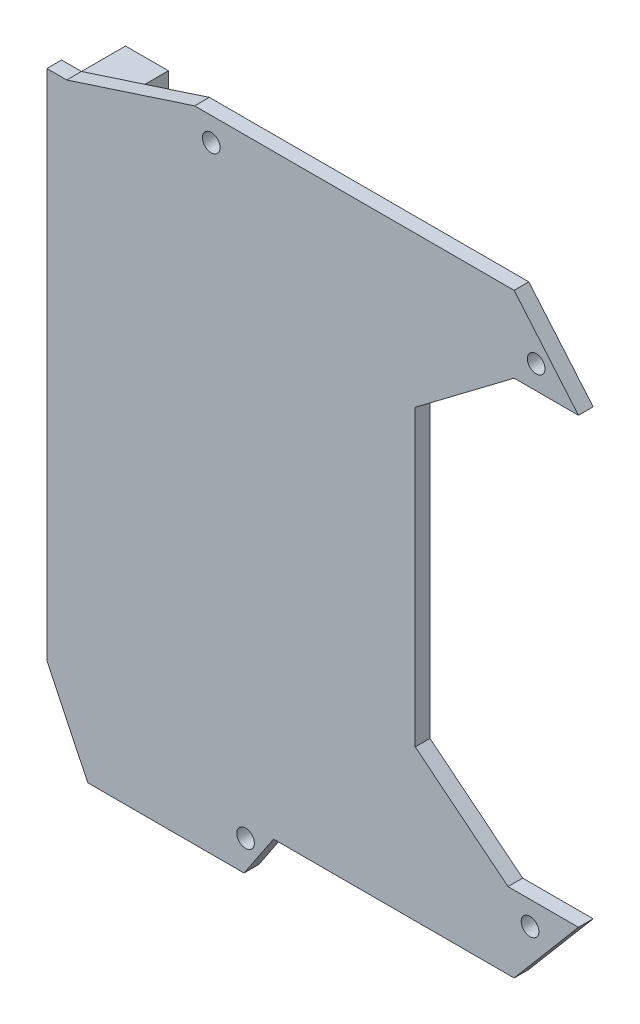
SolidWorks part; units mm, degrees
ref_plane "前视基准面" through (0, 0, 0) normal (0, 0, 1) x (1, 0, 0)
ref_plane "上视基准面" through (0, 0, 0) normal (0, 1, 0) x (1, 0, 0)
ref_plane "右视基准面" through (0, 0, 0) normal (1, 0, 0) x (0, 0, -1)
other "Configuration Table"
sketch "草图1" plane through (0, 0, 0) normal (0, 0, 1) x (1, 0, 0)
  line L0 (-117.8959, 10.15) -> (-117.8959, 50.15) construction
  line L1 (-117.8959, 10.15) -> (-117.8959, 50.15)
  line L3 (-104.45, 60.3) -> (-117.8959, 50.15)
  line L4 (-117.8959, 10.15) -> (-105.2853, 0)
  line L5 (-165.3, 65) -> (-168, 65)
  line L6 (-168, 65) -> (-168, -4.7)
  line L11 (-104.45, 68.85) -> (-104.45, 60.3)
  line L12 (-104.45, 60.3) -> (-95.7, 60.3)
  line L13 (-95.7, 60.3) -> (-104.45, 70.65)
  line L14 (-104.45, 70.65) -> (-147.9, 70.65)
  line L15 (-147.9, 70.65) -> (-165.3, 65)
  line L16 (-165.3, 65) -> (-159.4717, 65)
  line L17 (-159.4717, 65) -> (-149.4421, 68.2567)
  line L18 (-149.4421, 68.2567) -> (-149.4421, 63.85)
  line L19 (-149.4421, 63.85) -> (-141.4421, 63.85)
  line L20 (-141.4421, 63.85) -> (-141.4421, 68.85)
  line L21 (-141.4421, 68.85) -> (-104.45, 68.85)
  line L22 (-104.45, 68.85) -> (-104.45, 60.3)
  line L23 (-104.45, 60.3) -> (-95.7, 60.3)
  line L24 (-95.7, 60.3) -> (-104.45, 70.65)
  line L25 (-104.45, 70.65) -> (-147.9, 70.65)
  line L26 (-147.9, 70.65) -> (-165.3, 65)
  line L27 (-165.3, 65) -> (-159.4717, 65)
  line L28 (-159.4717, 65) -> (-149.4421, 68.2567)
  line L29 (-149.4421, 68.2567) -> (-149.4421, 63.85)
  line L30 (-149.4421, 63.85) -> (-141.4421, 63.85)
  line L31 (-141.4421, 63.85) -> (-141.4421, 68.85)
  line L32 (-141.4421, 68.85) -> (-104.45, 68.85)
  line L36 (-141.1744, -8.55) -> (-145.1744, -14.55)
  line L37 (-145.1744, -14.55) -> (-161.298, -14.55)
  line L38 (-161.298, -14.55) -> (-164.1652, -8.55)
  line L39 (-164.1652, -8.55) -> (-165.3, -8.55)
  line L40 (-165.3, -8.55) -> (-165.3, -4.7)
  line L41 (-165.3, -4.7) -> (-168, -4.7)
  line L42 (-168, -4.7) -> (-162.4327, -16.35)
  line L43 (-162.4327, -16.35) -> (-141.1744, -16.35)
  line L44 (-141.1744, -16.35) -> (-137.1744, -10.35)
  line L45 (-137.1744, -10.35) -> (-104.45, -10.35)
  line L46 (-104.45, -10.35) -> (-95.7, 0)
  line L47 (-95.7, 0) -> (-105.2853, 0)
  line L48 (-105.2853, 0) -> (-105.2853, -8.55)
  line L49 (-105.2853, -8.55) -> (-141.1744, -8.55)
  line L50 (-141.1744, -8.55) -> (-145.1744, -14.55)
  line L51 (-145.1744, -14.55) -> (-161.298, -14.55)
  line L52 (-161.298, -14.55) -> (-164.1652, -8.55)
  line L53 (-164.1652, -8.55) -> (-165.3, -8.55)
  line L54 (-165.3, -8.55) -> (-165.3, -4.7)
  line L55 (-165.3, -4.7) -> (-168, -4.7)
  line L56 (-168, -4.7) -> (-162.4327, -16.35)
  line L57 (-162.4327, -16.35) -> (-141.1744, -16.35)
  line L58 (-141.1744, -16.35) -> (-137.1744, -10.35)
  line L59 (-137.1744, -10.35) -> (-104.45, -10.35)
  line L60 (-104.45, -10.35) -> (-95.7, 0)
  line L61 (-95.7, 0) -> (-105.2853, 0)
  line L62 (-105.2853, 0) -> (-105.2853, -8.55)
  line L63 (-105.2853, -8.55) -> (-141.1744, -8.55)
  circle A0 centre (-145.6421, 67.45) radius 1.2 construction
  circle A1 centre (-145.6421, 67.45) radius 1.2
  circle A2 centre (-101.45, 63.5) radius 1.2 construction
  circle A3 centre (-101.45, 63.5) radius 1.2
  circle A4 centre (-102.2853, -3.2) radius 1.2 construction
  circle A5 centre (-102.2853, -3.2) radius 1.2
  circle A6 centre (-140.9744, -12.15) radius 1.2 construction
  circle A7 centre (-140.9744, -12.15) radius 1.2
  dimension "D1" = 0
  dimension "D2" = 0
extrude "凸台-拉伸1" add sketch "草图1" along normal blind 2 contours L63 L62 L4 L1 L3 L22 L32 L31 L30 L29 L28 L27 L5 L6 L55 L54 L53 L52 L51 L50 | L31 L32 L22 L23 L24 L25 L26 L27 L28 L29 L30 A3 A1 | L62 L63 L50 L51 L52 L53 L54 L55 L56 L57 L58 L59 L60 L61 A7 A5
sketch "草图2" plane through (0, 0, 0) normal (0, 0, -1) x (-1, 0, 0)
  line L0 (165.3, 65) -> (165.3, 59) construction
  line L1 (165.3, 65) -> (165.3, 59)
  line L2 (165.3, 1.3) -> (165.3, -4.7) construction
  line L3 (165.3, 1.3) -> (165.3, -4.7)
  line L4 (165.3, 59) -> (150.9, 59) construction
  line L5 (165.3, 59) -> (150.9, 59)
  line L6 (165.3, 1.3) -> (150.9, 1.3) construction
  line L7 (165.3, 1.3) -> (150.9, 1.3)
  line L8 (165.3, 59) -> (150.9, 59)
  line L10 (165.3, 65) -> (159.4717, 65)
  line L11 (165.3, 65) -> (165.3, 59)
  line L12 (165.3, 59) -> (159.4717, 59)
  line L13 (159.4717, 65) -> (159.4717, 59)
  line L14 (165.3, 1.3) -> (159.4717, 1.3)
  line L15 (104.45, 60.3) -> (117.8959, 50.15)
  line L16 (117.8959, 50.15) -> (117.8959, 10.15)
  line L17 (117.8959, 10.15) -> (105.2853, 0)
  line L18 (105.2853, 0) -> (95.7, 0)
  line L19 (95.7, 0) -> (104.45, -10.35)
  line L20 (104.45, -10.35) -> (137.1744, -10.35)
  line L21 (137.1744, -10.35) -> (141.1744, -16.35)
  line L22 (141.1744, -16.35) -> (162.4327, -16.35)
  line L23 (162.4327, -16.35) -> (168, -4.7)
  line L24 (168, -4.7) -> (168, 65)
  line L25 (168, 65) -> (165.3, 65)
  line L26 (165.3, 65) -> (147.9, 70.65)
  line L27 (147.9, 70.65) -> (104.45, 70.65)
  line L28 (104.45, 70.65) -> (95.7, 60.3)
  line L29 (95.7, 60.3) -> (104.45, 60.3)
  line L30 (104.45, 60.3) -> (117.8959, 50.15)
  line L31 (117.8959, 50.15) -> (117.8959, 10.15)
  line L32 (117.8959, 10.15) -> (105.2853, 0)
  line L33 (105.2853, 0) -> (95.7, 0)
  line L34 (95.7, 0) -> (104.45, -10.35)
  line L35 (104.45, -10.35) -> (137.1744, -10.35)
  line L36 (137.1744, -10.35) -> (141.1744, -16.35)
  line L37 (141.1744, -16.35) -> (162.4327, -16.35)
  line L38 (162.4327, -16.35) -> (168, -4.7)
  line L39 (168, -4.7) -> (168, 65)
  line L40 (168, 65) -> (165.3, 65)
  line L41 (165.3, 65) -> (147.9, 70.65)
  line L42 (147.9, 70.65) -> (104.45, 70.65)
  line L43 (104.45, 70.65) -> (95.7, 60.3)
  line L44 (95.7, 60.3) -> (104.45, 60.3)
  line L45 (165.3, 1.3) -> (165.3, -4.7)
  line L46 (165.3, -4.7) -> (159.4717, -4.7)
  line L47 (159.4717, 1.3) -> (159.4717, -4.7)
  dimension "D1" = 0
extrude "凸台-拉伸3" add sketch "草图2" along normal blind 6 contours L10 L13 L5 L1 | L7 L47 L46 L3
sketch "草图4" plane through (-165.3, 0, 0) normal (-1, 0, 0) x (0, 0, 1)
  circle A0 centre (-3.1, 61.9) radius 1.5 construction
  circle A1 centre (-3.1, 61.9) radius 1.5
  circle A2 centre (-3.1, -1.6) radius 1.5 construction
  circle A3 centre (-3.1, -1.6) radius 1.5
extrude "切除-拉伸1" cut sketch "草图4" against normal up to surface (5.8283 mm away) up to face at (-159.4717, -1.7, -3)
